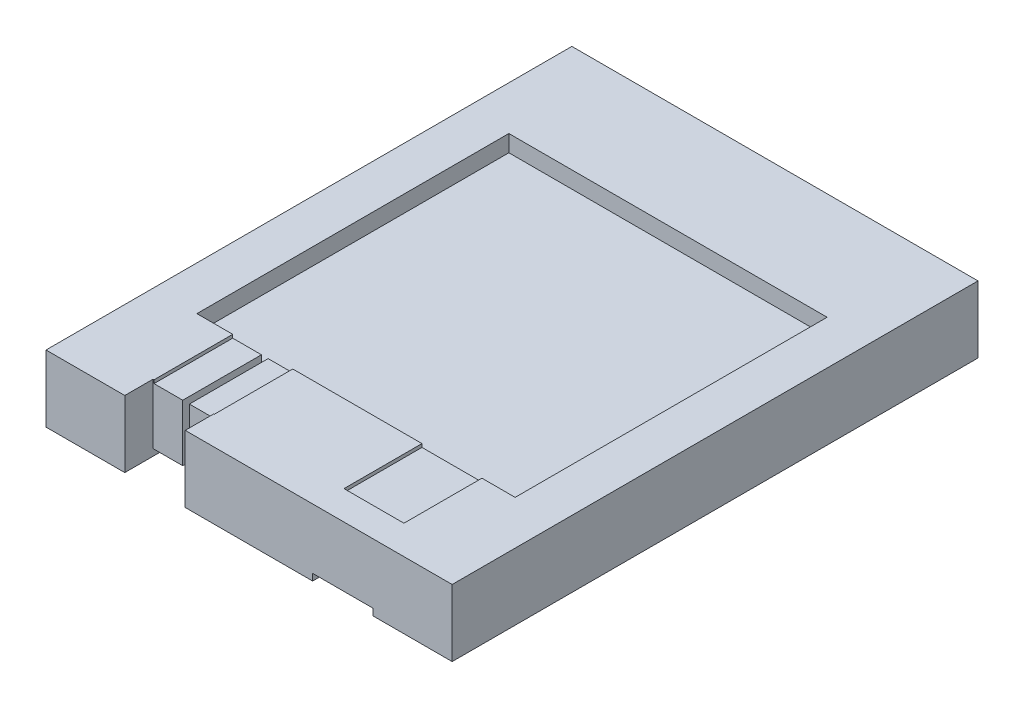
SolidWorks part; units mm, degrees
ref_plane "Front Plane" through (0, 0, 0) normal (0, 0, 1) x (1, 0, 0)
ref_plane "Top Plane" through (0, 0, 0) normal (0, 1, 0) x (1, 0, 0)
ref_plane "Right Plane" through (0, 0, 0) normal (1, 0, 0) x (0, 0, -1)
sketch "Sketch1" plane through (0, 0, 0) normal (0, 1, 0) x (1, 0, 0)
  line L1 (-60.802, -78.7194) -> (60.802, -78.7194)
  line L2 (-60.802, -78.7194) -> (-60.802, 78.7194)
  line L3 (-60.802, 78.7194) -> (60.802, 78.7194)
  line L4 (60.802, -78.7194) -> (60.802, 78.7194)
  line L5 (-60.802, -78.7194) -> (60.802, 78.7194) construction
  line L6 (-60.802, 78.7194) -> (60.802, -78.7194) construction
  point P0 (0, 0)
extrude "Boss-Extrude1" add sketch "Sketch1" along normal blind 20
sketch "Sketch2" plane through (0, 20, 0) normal (0, 1, 0) x (1, 0, 0)
  line L0 (-18.9364, -70.2667) -> (-36.9122, -70.2667)
  line L1 (37.6978, -70.0512) -> (19.7464, -70.0512)
  line L2 (37.6978, -70.0512) -> (37.6978, -46.515)
  line L3 (37.6978, -46.515) -> (19.7464, -46.515)
  line L4 (19.7464, -70.0512) -> (19.7464, -46.515)
  line L5 (37.6978, -70.0512) -> (19.7464, -46.515) construction
  line L6 (37.6978, -46.515) -> (19.7464, -70.0512) construction
  line L7 (-18.9364, -70.2667) -> (-18.9364, -46.6985)
  line L8 (-18.9364, -46.6985) -> (-36.9122, -46.6985)
  line L9 (-36.9122, -70.2667) -> (-36.9122, -46.6985)
  line L10 (-18.9364, -70.2667) -> (-36.9122, -46.6985) construction
  line L11 (-18.9364, -46.6985) -> (-36.9122, -70.2667) construction
  point P0 (28.7221, -58.2831)
  point P5 (-27.9243, -58.4826)
extrude "Cut-Extrude1" cut sketch "Sketch2" against normal blind 1
sketch "Sketch3" plane through (0, 20, 0) normal (0, 1, 0) x (1, 0, 0)
  line L1 (-47.6429, 46.7028) -> (47.6429, 46.7028)
  line L2 (-47.6429, 46.7028) -> (-47.6429, -46.7028)
  line L3 (-47.6429, -46.7028) -> (47.6429, -46.7028)
  line L4 (47.6429, 46.7028) -> (47.6429, -46.7028)
  line L5 (-47.6429, 46.7028) -> (47.6429, -46.7028) construction
  line L6 (-47.6429, -46.7028) -> (47.6429, 46.7028) construction
  point P0 (0, 0)
extrude "Cut-Extrude2" cut sketch "Sketch3" against normal blind 5
sketch "Sketch5" plane through (0, 0, 0) normal (0, -1, 0) x (1, 0, 0)
  line L0 (-60.802, 78.7194) -> (60.802, 78.7194) construction
  line L1 (-37.2136, 78.7194) -> (-19.1136, 78.7194)
  line L2 (-37.2136, 78.7194) -> (-37.2136, -78.7194)
  line L3 (-37.2136, -78.7194) -> (-19.1136, -78.7194)
  line L4 (-19.1136, 78.7194) -> (-19.1136, -78.7194)
  line L5 (60.802, -78.7194) -> (-60.802, -78.7194) construction
  line L6 (19.0304, 78.8562) -> (37.1304, 78.8562)
  line L7 (19.0304, 78.8562) -> (19.0304, -78.5827)
  line L8 (19.0304, -78.5827) -> (37.1304, -78.5827)
  line L9 (37.1304, 78.8562) -> (37.1304, -78.5827)
  dimension "D1" = 18.1
  dimension "D2" = 18.1
extrude "Cut-Extrude3" cut sketch "Sketch5" against normal blind 2
ref_plane "Plane1" through (-36.9122, 20, 46.7028) normal (0, 0, 1) x (1, 0, 0)
sketch "Sketch6" plane through (-36.9122, 20, 46.7028) normal (0, 0, 1) x (1, 0, 0)
  line L0 (-0.3015, -18) -> (-0.3015, -20) construction
  line L1 (8.5985, -18) -> (10.5985, -18)
  line L2 (8.5985, -18) -> (8.5985, 0)
  line L3 (8.5985, 0) -> (10.5985, 0)
  line L4 (10.5985, -18) -> (10.5985, 0)
  line L5 (17.7985, -18) -> (-0.3015, -18) construction
  line L6 (-23.8898, 0) -> (97.7141, 0) construction
  dimension "D1" = 2
  dimension "D2" = 0
  dimension "D3" = 8.9
  dimension "D4" = 0
extrude "Cut-Extrude4" cut sketch "Sketch6" along normal blind 33
sketch "Sketch8" plane through (0, 0, 78.7194) normal (0, 0, 1) x (1, 0, 0)
  line L0 (-60.802, 20) -> (-28.3136, 20) construction
  line L1 (-19.1136, 2) -> (-37.2136, 2)
  line L2 (-19.1136, 2) -> (-19.1136, 20)
  line L3 (-19.1136, 20) -> (-37.2136, 20)
  line L4 (-37.2136, 2) -> (-37.2136, 20)
  line L5 (-37.2136, 2) -> (-37.2136, 0) construction
  dimension "D1" = 0
extrude "Cut-Extrude5" cut sketch "Sketch8" against normal up to surface (8.4527 mm away) up to face at (-32.6129, 19.5, 70.2667)
